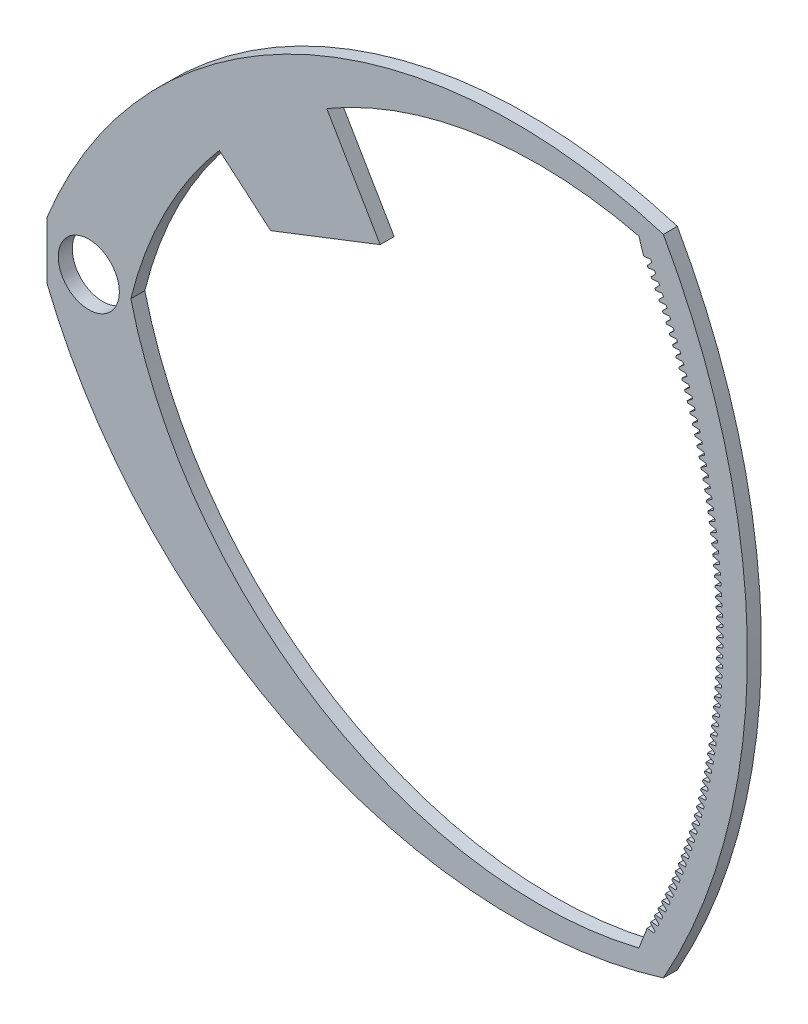
SolidWorks part; units mm, degrees
ref_plane "Plane1" through (0, 0, 0) normal (0, 0, 1) x (1, 0, 0)
ref_plane "Plane2" through (0, 0, 0) normal (0, 1, 0) x (1, 0, 0)
ref_plane "Plane3" through (0, 0, 0) normal (1, 0, 0) x (0, 0, -1)
sketch "Sketch3" plane through (0, 0, 0) normal (0, 0, 1) x (1, 0, 0)
  line L0 (0, 0) -> (305.6191, 0) construction
  line L2 (196.2779, 110) -> (205.0013, 114.8889) construction
  line L5 (-15, -10) -> (-15, 10)
  line L13 (64.9047, 45.9884) -> (103.9541, 61.1877) construction
  line L15 (84.9015, 93.7316) -> (34.4406, 64.1896) construction
  line L16 (46.566, 61.632) -> (12.1811, 21.323) construction
  line L19 (226.2435, 1.7084) -> (223.986, 2.5016)
  line L20 (224, 0) -> (226.2485, 0.8184)
  line L21 (224.9781, 3.1415) -> (0, 0) construction
  line L22 (223.9782, 3.1275) -> (226.215, 3.9772)
  line L23 (226.1976, 4.8671) -> (223.9293, 5.6287)
  line L24 (223.9127, 6.2544) -> (226.1375, 7.1353)
  line L25 (226.1076, 8.0248) -> (223.8289, 8.7547)
  line L26 (223.8035, 9.3801) -> (226.0158, 10.292)
  line L27 (225.9736, 11.181) -> (223.6848, 11.879)
  line L28 (223.6507, 12.504) -> (225.8501, 13.4467)
  line L29 (225.7954, 14.335) -> (223.4971, 15.001)
  line L30 (223.4543, 15.6255) -> (225.6403, 16.5987)
  line L31 (225.5733, 17.4862) -> (223.2659, 18.12)
  line L32 (223.2144, 18.7438) -> (225.3866, 19.7475)
  line L33 (225.3071, 20.634) -> (222.9911, 21.2355)
  line L34 (222.9309, 21.8586) -> (225.0889, 22.8925)
  line L35 (224.9971, 23.7777) -> (222.6729, 24.3469)
  line L36 (222.604, 24.969) -> (224.7473, 26.033)
  line L37 (224.6431, 26.9169) -> (222.3113, 27.4535)
  line L38 (222.2337, 28.0746) -> (224.3619, 29.1684)
  line L39 (224.2454, 30.0508) -> (221.9063, 30.5548)
  line L40 (221.82, 31.1748) -> (223.9328, 32.2981)
  line L41 (223.804, 33.1788) -> (221.4581, 33.6501)
  line L42 (221.3632, 34.2688) -> (223.46, 35.4216)
  line L43 (223.3189, 36.3003) -> (220.9666, 36.7389)
  line L44 (220.8631, 37.3562) -> (222.9437, 38.5381)
  line L45 (222.7903, 39.4148) -> (220.4321, 39.8205)
  line L46 (220.32, 40.4363) -> (222.3839, 41.6471)
  line L47 (222.2183, 42.5216) -> (219.8547, 42.8943)
  line L48 (219.734, 43.5085) -> (221.7807, 44.748)
  line L49 (221.6029, 45.6201) -> (219.2343, 45.9598)
  line L50 (219.1051, 46.5722) -> (221.1343, 47.8402)
  line L51 (220.9444, 48.7097) -> (218.5713, 49.0163)
  line L52 (218.4335, 49.6269) -> (220.4448, 50.9231)
  line L53 (220.2428, 51.7899) -> (217.8656, 52.0632)
  line L54 (217.7193, 52.6718) -> (219.7123, 53.996)
  line L55 (219.4982, 54.8599) -> (217.1174, 55.1)
  line L56 (216.9626, 55.7065) -> (218.937, 57.0584)
  line L57 (218.7108, 57.9192) -> (216.327, 58.1261)
  line L58 (216.1637, 58.7304) -> (218.119, 60.1097)
  line L59 (217.8808, 60.9672) -> (215.4943, 61.1408)
  line L60 (215.3226, 61.7428) -> (217.2585, 63.1492)
  line L61 (217.0084, 64.0034) -> (214.6196, 64.1436)
  line L62 (214.4396, 64.7431) -> (216.3556, 66.1765)
  line L63 (216.0936, 67.0271) -> (213.7031, 67.1339)
  line L64 (213.5147, 67.7309) -> (215.4105, 69.1908)
  line L65 (215.1367, 70.0377) -> (212.745, 70.1112)
  line L66 (212.5482, 70.7054) -> (214.4235, 72.1917)
  line L67 (214.1378, 73.0346) -> (211.7453, 73.0747)
  line L68 (211.5403, 73.6661) -> (213.3946, 75.1785)
  line L69 (213.0972, 76.0173) -> (210.7044, 76.024)
  line L70 (210.4911, 76.6125) -> (212.3242, 78.1506)
  line L71 (212.0151, 78.9852) -> (209.6224, 78.9585)
  line L72 (209.401, 79.544) -> (211.2123, 81.1075)
  line L73 (210.8916, 81.9377) -> (208.4995, 81.8776)
  line L74 (208.2699, 82.4599) -> (210.0593, 84.0486)
  line L75 (209.727, 84.8742) -> (207.336, 84.7807)
  line L76 (207.0983, 85.3598) -> (208.8653, 86.9733)
  line L77 (208.5216, 87.7942) -> (206.1321, 87.6673)
  line L78 (205.8863, 88.243) -> (207.6306, 89.881)
  line L79 (207.2754, 90.6971) -> (204.888, 90.5368)
  line L80 (204.6342, 91.109) -> (206.3554, 92.7712)
  line L81 (205.9889, 93.5822) -> (203.6039, 93.3887)
  line L82 (203.3422, 93.9573) -> (205.04, 95.6433)
  line L83 (204.6622, 96.4492) -> (202.2802, 96.2223)
  line L84 (202.0105, 96.7872) -> (203.6847, 98.4968)
  line L85 (203.2956, 99.2973) -> (200.917, 99.0372)
  line L86 (200.6394, 99.5983) -> (202.2896, 101.3311)
  line L87 (201.8894, 102.1261) -> (199.5146, 101.8328)
  line L88 (199.2293, 102.3899) -> (200.8551, 104.1456)
  line L89 (200.4438, 104.9349) -> (198.0734, 104.6085)
  line L90 (197.7803, 105.1616) -> (196.2779, 110)
  line L91 (226.2453, -1.4506) -> (223.9991, -0.626)
  line L92 (223.9782, -3.1275) -> (226.2379, -2.3406)
  line L93 (226.203, -4.6094) -> (223.9686, -3.7534)
  line L94 (223.9127, -6.2544) -> (226.1832, -5.4992)
  line L95 (226.1166, -7.7672) -> (223.8943, -6.8801)
  line L96 (223.8035, -9.3801) -> (226.0843, -8.6566)
  line L97 (225.9861, -10.9235) -> (223.7764, -10.0055)
  line L98 (223.6507, -12.504) -> (225.9414, -11.8124)
  line L99 (225.8116, -14.0777) -> (223.6149, -13.1289)
  line L100 (223.4543, -15.6255) -> (225.7545, -14.9659)
  line L101 (225.593, -17.2292) -> (223.4098, -16.2498)
  line L102 (223.2144, -18.7438) -> (225.5235, -18.1165)
  line L103 (225.3305, -20.3773) -> (223.1612, -19.3675)
  line L104 (222.9309, -21.8586) -> (225.2486, -21.2635)
  line L105 (225.024, -23.5214) -> (222.869, -22.4814)
  line L106 (222.604, -24.969) -> (224.9297, -24.4064)
  line L107 (224.6737, -26.6609) -> (222.5334, -25.591)
  line L108 (222.2337, -28.0746) -> (224.5671, -27.5445)
  line L109 (224.2795, -29.7952) -> (222.1544, -28.6955)
  line L110 (221.82, -31.1748) -> (224.1606, -30.6773)
  line L111 (223.8417, -32.9238) -> (221.7321, -31.7945)
  line L112 (221.3632, -34.2688) -> (223.7104, -33.8041)
  line L113 (223.3602, -36.0459) -> (221.2665, -34.8873)
  line L114 (220.8631, -37.3562) -> (223.2166, -36.9242)
  line L115 (222.8351, -39.161) -> (220.7579, -37.9732)
  line L116 (220.32, -40.4363) -> (222.6793, -40.0372)
  line L117 (222.2666, -42.2684) -> (220.2062, -41.0518)
  line L118 (219.734, -43.5085) -> (222.0986, -43.1424)
  line L119 (221.6548, -45.3676) -> (219.6115, -44.1224)
  line L120 (219.1051, -46.5722) -> (221.4746, -46.2392)
  line L121 (220.9997, -48.458) -> (218.9741, -47.1843)
  line L122 (218.4335, -49.6269) -> (220.8074, -49.327)
  line L123 (220.3016, -51.5389) -> (218.2939, -50.2371)
  line L124 (217.7193, -52.6718) -> (220.0972, -52.4051)
  line L125 (219.5606, -54.6098) -> (217.5712, -53.28)
  line L126 (216.9626, -55.7065) -> (219.344, -55.473)
  line L127 (218.7767, -57.67) -> (216.8061, -56.3126)
  line L128 (216.1637, -58.7304) -> (218.5481, -58.5301)
  line L129 (217.9502, -60.719) -> (215.9987, -59.3342)
  line L130 (215.3226, -61.7428) -> (217.7096, -61.5759)
  line L131 (217.0811, -63.7561) -> (215.1492, -62.3442)
  line L132 (214.4396, -64.7431) -> (216.8287, -64.6096)
  line L133 (216.1698, -66.7808) -> (214.2578, -65.3421)
  line L134 (213.5147, -67.7309) -> (215.9054, -67.6307)
  line L135 (215.2163, -69.7925) -> (213.3246, -68.3272)
  line L136 (212.5482, -70.7054) -> (214.9401, -70.6386)
  line L137 (214.2209, -72.7906) -> (212.3498, -71.2991)
  line L138 (211.5403, -73.6661) -> (213.9329, -73.6327)
  line L139 (213.1837, -75.7745) -> (211.3336, -74.257)
  line L140 (210.4911, -76.6125) -> (212.884, -76.6125)
  line L141 (212.1049, -78.7436) -> (210.2762, -77.2004)
  line L142 (209.401, -79.544) -> (211.7935, -79.5774)
  line L143 (210.9848, -81.6974) -> (209.1779, -80.1288)
  line L144 (208.2699, -82.4599) -> (210.6618, -82.5267)
  line L145 (209.8236, -84.6352) -> (208.0387, -83.0416)
  line L146 (207.0983, -85.3598) -> (209.489, -85.46)
  line L147 (208.6215, -87.5566) -> (206.859, -85.9382)
  line L148 (205.8863, -88.243) -> (208.2754, -88.3766)
  line L149 (207.3786, -90.4608) -> (205.6389, -88.818)
  line L150 (204.6342, -91.109) -> (207.0212, -91.2759)
  line L151 (206.0954, -93.3475) -> (204.3788, -91.6805)
  line L152 (203.3422, -93.9573) -> (205.7266, -94.1575)
  line L153 (204.772, -96.2159) -> (203.0788, -94.5251)
  line L154 (202.0105, -96.7872) -> (204.3919, -97.0207)
  line L155 (203.4086, -99.0656) -> (201.7392, -97.3513)
  line L156 (200.6394, -99.5983) -> (203.0173, -99.865)
  line L157 (202.0056, -101.896) -> (200.3603, -100.1586)
  line L158 (199.2293, -102.3899) -> (201.6032, -102.6898)
  line L159 (199.2293, -102.3899) -> (196.2779, -110)
  line L160 (46.566, 61.632) -> (64.9047, 45.9884) construction
  line L161 (84.9015, 93.7316) -> (103.9541, 61.1877) construction
  line L162 (0, 0) -> (196.2779, 110) construction
  line L163 (46.566, 61.632) -> (64.9047, 45.9884)
  line L164 (64.9047, 45.9884) -> (103.9541, 61.1877)
  line L165 (103.9541, 61.1877) -> (84.9015, 93.7316)
  line L166 (196.2779, 110) -> (117.1942, 79.2181) construction
  arc A0 (205.0013, -114.8889) -> (205.0013, 114.8889) centre (0, 0) ccw
  arc A1 (220.8879, 48.9651) -> (225.6282, -16.7623) centre (0, 0) cw construction
  arc A2 (196.2779, 110) -> (196.2779, -110) centre (0, 0) cw construction
  circle A3 centre (0, 0) radius 10.9
  circle A4 centre (100, 0) radius 70 construction
  arc A5 (15, 0) -> (196.2779, 110) centre (160.6858, -35.7162) cw construction
  arc A6 (-15, 10) -> (205.0013, 114.8889) centre (152.0118, -57.1347) cw
  arc A7 (-15, -10) -> (205.0013, -114.8889) centre (152.0118, 57.1347) ccw
  arc A9 (15, 0) -> (46.566, 61.632) centre (160.6858, -35.7162) cw
  arc A10 (84.9015, 93.7316) -> (196.2779, 110) centre (160.6858, -35.7162) cw
  arc A12 (100, 0) -> (46.366, 88.6013) centre (0, 0) ccw construction
  arc A16 (223.2671, -18.1055) -> (218.4, 49.774) centre (0, 0) ccw construction
  arc A17 (223.9782, 3.1275) -> (223.986, 2.5016) centre (0, 0) cw
  arc A18 (226.2485, 0.8184) -> (226.2435, 1.7084) centre (0, 0) ccw
  arc A19 (226.215, 3.9772) -> (226.1976, 4.8671) centre (0, 0) ccw
  arc A20 (223.9127, 6.2544) -> (223.9293, 5.6287) centre (0, 0) cw
  arc A21 (226.1375, 7.1353) -> (226.1076, 8.0248) centre (0, 0) ccw
  arc A22 (223.8035, 9.3801) -> (223.8289, 8.7547) centre (0, 0) cw
  arc A23 (226.0158, 10.292) -> (225.9736, 11.181) centre (0, 0) ccw
  arc A24 (223.6507, 12.504) -> (223.6848, 11.879) centre (0, 0) cw
  arc A25 (225.8501, 13.4467) -> (225.7954, 14.335) centre (0, 0) ccw
  arc A26 (223.4543, 15.6255) -> (223.4971, 15.001) centre (0, 0) cw
  arc A27 (225.6403, 16.5987) -> (225.5733, 17.4862) centre (0, 0) ccw
  arc A28 (223.2144, 18.7438) -> (223.2659, 18.12) centre (0, 0) cw
  arc A29 (225.3866, 19.7475) -> (225.3071, 20.634) centre (0, 0) ccw
  arc A30 (222.9309, 21.8586) -> (222.9911, 21.2355) centre (0, 0) cw
  arc A31 (225.0889, 22.8925) -> (224.9971, 23.7777) centre (0, 0) ccw
  arc A32 (222.604, 24.969) -> (222.6729, 24.3469) centre (0, 0) cw
  arc A33 (224.7473, 26.033) -> (224.6431, 26.9169) centre (0, 0) ccw
  arc A34 (222.2337, 28.0746) -> (222.3113, 27.4535) centre (0, 0) cw
  arc A35 (224.3619, 29.1684) -> (224.2454, 30.0508) centre (0, 0) ccw
  arc A36 (221.82, 31.1748) -> (221.9063, 30.5548) centre (0, 0) cw
  arc A37 (223.9328, 32.2981) -> (223.804, 33.1788) centre (0, 0) ccw
  arc A38 (221.3632, 34.2688) -> (221.4581, 33.6501) centre (0, 0) cw
  arc A39 (223.46, 35.4216) -> (223.3189, 36.3003) centre (0, 0) ccw
  arc A40 (220.8631, 37.3562) -> (220.9666, 36.7389) centre (0, 0) cw
  arc A41 (222.9437, 38.5381) -> (222.7903, 39.4148) centre (0, 0) ccw
  arc A42 (220.32, 40.4363) -> (220.4321, 39.8205) centre (0, 0) cw
  arc A43 (222.3839, 41.6471) -> (222.2183, 42.5216) centre (0, 0) ccw
  arc A44 (219.734, 43.5085) -> (219.8547, 42.8943) centre (0, 0) cw
  arc A45 (221.7807, 44.748) -> (221.6029, 45.6201) centre (0, 0) ccw
  arc A46 (219.1051, 46.5722) -> (219.2343, 45.9598) centre (0, 0) cw
  arc A47 (221.1343, 47.8402) -> (220.9444, 48.7097) centre (0, 0) ccw
  arc A48 (218.4335, 49.6269) -> (218.5713, 49.0163) centre (0, 0) cw
  arc A49 (220.4448, 50.9231) -> (220.2428, 51.7899) centre (0, 0) ccw
  arc A50 (217.7193, 52.6718) -> (217.8656, 52.0632) centre (0, 0) cw
  arc A51 (219.7123, 53.996) -> (219.4982, 54.8599) centre (0, 0) ccw
  arc A52 (216.9626, 55.7065) -> (217.1174, 55.1) centre (0, 0) cw
  arc A53 (218.937, 57.0584) -> (218.7108, 57.9192) centre (0, 0) ccw
  arc A54 (216.1637, 58.7304) -> (216.327, 58.1261) centre (0, 0) cw
  arc A55 (218.119, 60.1097) -> (217.8808, 60.9672) centre (0, 0) ccw
  arc A56 (215.3226, 61.7428) -> (215.4943, 61.1408) centre (0, 0) cw
  arc A57 (217.2585, 63.1492) -> (217.0084, 64.0034) centre (0, 0) ccw
  arc A58 (214.4396, 64.7431) -> (214.6196, 64.1436) centre (0, 0) cw
  arc A59 (216.3556, 66.1765) -> (216.0936, 67.0271) centre (0, 0) ccw
  arc A60 (213.5147, 67.7309) -> (213.7031, 67.1339) centre (0, 0) cw
  arc A61 (215.4105, 69.1908) -> (215.1367, 70.0377) centre (0, 0) ccw
  arc A62 (212.5482, 70.7054) -> (212.745, 70.1112) centre (0, 0) cw
  arc A63 (214.4235, 72.1917) -> (214.1378, 73.0346) centre (0, 0) ccw
  arc A64 (211.5403, 73.6661) -> (211.7453, 73.0747) centre (0, 0) cw
  arc A65 (213.3946, 75.1785) -> (213.0972, 76.0173) centre (0, 0) ccw
  arc A66 (210.4911, 76.6125) -> (210.7044, 76.024) centre (0, 0) cw
  arc A67 (212.3242, 78.1506) -> (212.0151, 78.9852) centre (0, 0) ccw
  arc A68 (209.401, 79.544) -> (209.6224, 78.9585) centre (0, 0) cw
  arc A69 (211.2123, 81.1075) -> (210.8916, 81.9377) centre (0, 0) ccw
  arc A70 (208.2699, 82.4599) -> (208.4995, 81.8776) centre (0, 0) cw
  arc A71 (210.0593, 84.0486) -> (209.727, 84.8742) centre (0, 0) ccw
  arc A72 (207.0983, 85.3598) -> (207.336, 84.7807) centre (0, 0) cw
  arc A73 (208.8653, 86.9733) -> (208.5216, 87.7942) centre (0, 0) ccw
  arc A74 (205.8863, 88.243) -> (206.1321, 87.6673) centre (0, 0) cw
  arc A75 (207.6306, 89.881) -> (207.2754, 90.6971) centre (0, 0) ccw
  arc A76 (204.6342, 91.109) -> (204.888, 90.5368) centre (0, 0) cw
  arc A77 (206.3554, 92.7712) -> (205.9889, 93.5822) centre (0, 0) ccw
  arc A78 (203.3422, 93.9573) -> (203.6039, 93.3887) centre (0, 0) cw
  arc A79 (205.04, 95.6433) -> (204.6622, 96.4492) centre (0, 0) ccw
  arc A80 (202.0105, 96.7872) -> (202.2802, 96.2223) centre (0, 0) cw
  arc A81 (203.6847, 98.4968) -> (203.2956, 99.2973) centre (0, 0) ccw
  arc A82 (200.6394, 99.5983) -> (200.917, 99.0372) centre (0, 0) cw
  arc A83 (202.2896, 101.3311) -> (201.8894, 102.1261) centre (0, 0) ccw
  arc A84 (199.2293, 102.3899) -> (199.5146, 101.8328) centre (0, 0) cw
  arc A85 (200.8551, 104.1456) -> (200.4438, 104.9349) centre (0, 0) ccw
  arc A86 (197.7803, 105.1616) -> (198.0734, 104.6085) centre (0, 0) cw
  arc A87 (224, 0) -> (223.9991, -0.626) centre (0, 0) cw
  arc A88 (226.2379, -2.3406) -> (226.2453, -1.4506) centre (0, 0) ccw
  arc A89 (223.9782, -3.1275) -> (223.9686, -3.7534) centre (0, 0) cw
  arc A90 (226.1832, -5.4992) -> (226.203, -4.6094) centre (0, 0) ccw
  arc A91 (223.9127, -6.2544) -> (223.8943, -6.8801) centre (0, 0) cw
  arc A92 (226.0843, -8.6566) -> (226.1166, -7.7672) centre (0, 0) ccw
  arc A93 (223.8035, -9.3801) -> (223.7764, -10.0055) centre (0, 0) cw
  arc A94 (225.9414, -11.8124) -> (225.9861, -10.9235) centre (0, 0) ccw
  arc A95 (223.6507, -12.504) -> (223.6149, -13.1289) centre (0, 0) cw
  arc A96 (225.7545, -14.9659) -> (225.8116, -14.0777) centre (0, 0) ccw
  arc A97 (223.4543, -15.6255) -> (223.4098, -16.2498) centre (0, 0) cw
  arc A98 (225.5235, -18.1165) -> (225.593, -17.2292) centre (0, 0) ccw
  arc A99 (223.2144, -18.7438) -> (223.1612, -19.3675) centre (0, 0) cw
  arc A100 (225.2486, -21.2635) -> (225.3305, -20.3773) centre (0, 0) ccw
  arc A101 (222.9309, -21.8586) -> (222.869, -22.4814) centre (0, 0) cw
  arc A102 (224.9297, -24.4064) -> (225.024, -23.5214) centre (0, 0) ccw
  arc A103 (222.604, -24.969) -> (222.5334, -25.591) centre (0, 0) cw
  arc A104 (224.5671, -27.5445) -> (224.6737, -26.6609) centre (0, 0) ccw
  arc A105 (222.2337, -28.0746) -> (222.1544, -28.6955) centre (0, 0) cw
  arc A106 (224.1606, -30.6773) -> (224.2795, -29.7952) centre (0, 0) ccw
  arc A107 (221.82, -31.1748) -> (221.7321, -31.7945) centre (0, 0) cw
  arc A108 (223.7104, -33.8041) -> (223.8417, -32.9238) centre (0, 0) ccw
  arc A109 (221.3632, -34.2688) -> (221.2665, -34.8873) centre (0, 0) cw
  arc A110 (223.2166, -36.9242) -> (223.3602, -36.0459) centre (0, 0) ccw
  arc A111 (220.8631, -37.3562) -> (220.7579, -37.9732) centre (0, 0) cw
  arc A112 (222.6793, -40.0372) -> (222.8351, -39.161) centre (0, 0) ccw
  arc A113 (220.32, -40.4363) -> (220.2062, -41.0518) centre (0, 0) cw
  arc A114 (222.0986, -43.1424) -> (222.2666, -42.2684) centre (0, 0) ccw
  arc A115 (219.734, -43.5085) -> (219.6115, -44.1224) centre (0, 0) cw
  arc A116 (221.4746, -46.2392) -> (221.6548, -45.3676) centre (0, 0) ccw
  arc A117 (219.1051, -46.5722) -> (218.9741, -47.1843) centre (0, 0) cw
  arc A118 (220.8074, -49.327) -> (220.9997, -48.458) centre (0, 0) ccw
  arc A119 (218.4335, -49.6269) -> (218.2939, -50.2371) centre (0, 0) cw
  arc A120 (220.0972, -52.4051) -> (220.3016, -51.5389) centre (0, 0) ccw
  arc A121 (217.7193, -52.6718) -> (217.5712, -53.28) centre (0, 0) cw
  arc A122 (219.344, -55.473) -> (219.5606, -54.6098) centre (0, 0) ccw
  arc A123 (216.9626, -55.7065) -> (216.8061, -56.3126) centre (0, 0) cw
  arc A124 (218.5481, -58.5301) -> (218.7767, -57.67) centre (0, 0) ccw
  arc A125 (216.1637, -58.7304) -> (215.9987, -59.3342) centre (0, 0) cw
  arc A126 (217.7096, -61.5759) -> (217.9502, -60.719) centre (0, 0) ccw
  arc A127 (215.3226, -61.7428) -> (215.1492, -62.3442) centre (0, 0) cw
  arc A128 (216.8287, -64.6096) -> (217.0811, -63.7561) centre (0, 0) ccw
  arc A129 (214.4396, -64.7431) -> (214.2578, -65.3421) centre (0, 0) cw
  arc A130 (215.9054, -67.6307) -> (216.1698, -66.7808) centre (0, 0) ccw
  arc A131 (213.5147, -67.7309) -> (213.3246, -68.3272) centre (0, 0) cw
  arc A132 (214.9401, -70.6386) -> (215.2163, -69.7925) centre (0, 0) ccw
  arc A133 (212.5482, -70.7054) -> (212.3498, -71.2991) centre (0, 0) cw
  arc A134 (213.9329, -73.6327) -> (214.2209, -72.7906) centre (0, 0) ccw
  arc A135 (211.5403, -73.6661) -> (211.3336, -74.257) centre (0, 0) cw
  arc A136 (212.884, -76.6125) -> (213.1837, -75.7745) centre (0, 0) ccw
  arc A137 (210.4911, -76.6125) -> (210.2762, -77.2004) centre (0, 0) cw
  arc A138 (211.7935, -79.5774) -> (212.1049, -78.7436) centre (0, 0) ccw
  arc A139 (209.401, -79.544) -> (209.1779, -80.1288) centre (0, 0) cw
  arc A140 (210.6618, -82.5267) -> (210.9848, -81.6974) centre (0, 0) ccw
  arc A141 (208.2699, -82.4599) -> (208.0387, -83.0416) centre (0, 0) cw
  arc A142 (209.489, -85.46) -> (209.8236, -84.6352) centre (0, 0) ccw
  arc A143 (207.0983, -85.3598) -> (206.859, -85.9382) centre (0, 0) cw
  arc A144 (208.2754, -88.3766) -> (208.6215, -87.5566) centre (0, 0) ccw
  arc A145 (205.8863, -88.243) -> (205.6389, -88.818) centre (0, 0) cw
  arc A146 (207.0212, -91.2759) -> (207.3786, -90.4608) centre (0, 0) ccw
  arc A147 (204.6342, -91.109) -> (204.3788, -91.6805) centre (0, 0) cw
  arc A148 (205.7266, -94.1575) -> (206.0954, -93.3475) centre (0, 0) ccw
  arc A149 (203.3422, -93.9573) -> (203.0788, -94.5251) centre (0, 0) cw
  arc A150 (204.3919, -97.0207) -> (204.772, -96.2159) centre (0, 0) ccw
  arc A151 (202.0105, -96.7872) -> (201.7392, -97.3513) centre (0, 0) cw
  arc A152 (203.0173, -99.865) -> (203.4086, -99.0656) centre (0, 0) ccw
  arc A153 (200.6394, -99.5983) -> (200.3603, -100.1586) centre (0, 0) cw
  arc A154 (201.6032, -102.6898) -> (202.0056, -101.896) centre (0, 0) ccw
  arc A155 (15, 0) -> (196.2779, -110) centre (160.6858, 35.7162) ccw
  point P3 (116.0077, 82.4599)
  point P9 (224.9997, 0.3639)
  point P12 (84.4294, 53.588)
  point P41 (224.9897, 2.149)
  point P218 (0, 0)
  point P355 (0, 0)
  dimension "D1" = 10
  dimension "D2" = 140
  dimension "D4" = 15
  dimension "D7" = 50
  dimension "D9" = 150
  dimension "D10" = 180
  dimension "D11" = 10
  dimension "D13" = 1
  dimension "D14" = 1.25
  dimension "D15" = 225
  dimension "D16" = 0.8
  dimension "D21" = 21.8
  dimension "D3" = 100
  dimension "D5" = 15
  dimension "D6" = 20
  dimension "D8" = 8
  dimension "D12" = 20
  dimension "D17" = 0.89
  dimension "D19" = 110
  dimension "D20" = 35
  dimension "D22" = 12
  dimension "D18" = 35
extrude "Boss-Extrude2" add sketch "Sketch3" along normal blind 5
